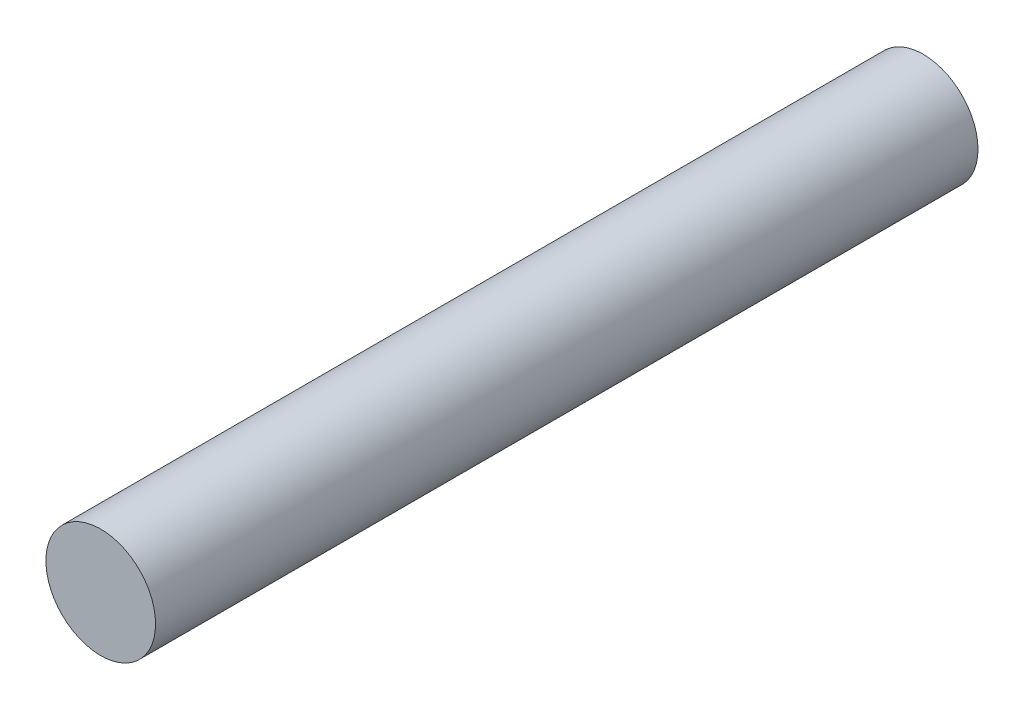
SolidWorks part; units mm, degrees
ref_plane "Front Plane" through (0, 0, 0) normal (0, 0, 1) x (1, 0, 0)
ref_plane "Top Plane" through (0, 0, 0) normal (0, 1, 0) x (1, 0, 0)
ref_plane "Right Plane" through (0, 0, 0) normal (1, 0, 0) x (0, 0, -1)
sketch "Sketch1" plane through (0, 0, 0) normal (0, 0, 1) x (1, 0, 0)
  circle A0 centre (0, 0) radius 25.4
  dimension "D1" = 50.8
extrude "Boss-Extrude1" add sketch "Sketch1" along normal blind 381
